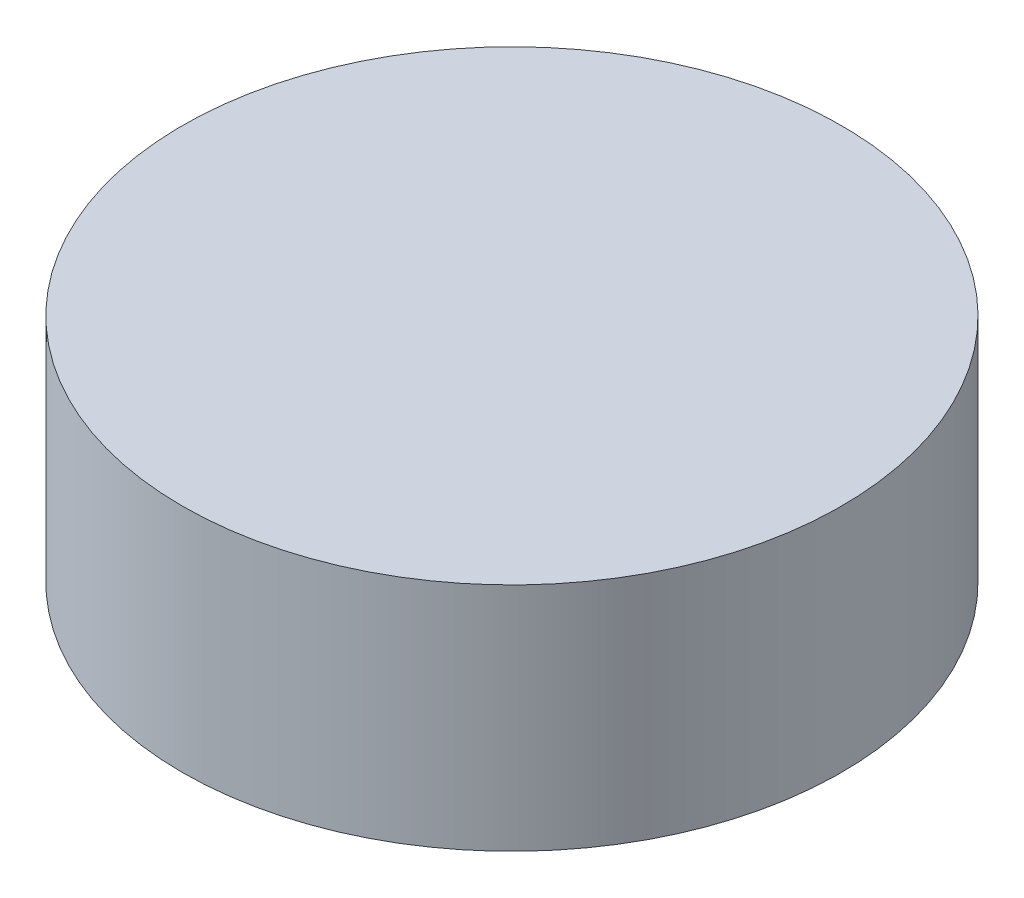
SolidWorks part; units mm, degrees
ref_plane "前视基准面" through (0, 0, 0) normal (0, 0, 1) x (1, 0, 0)
ref_plane "上视基准面" through (0, 0, 0) normal (0, 1, 0) x (1, 0, 0)
ref_plane "右视基准面" through (0, 0, 0) normal (1, 0, 0) x (0, 0, -1)
sketch "Sketch1" plane through (0, 0, 0) normal (0, 1, 0) x (1, 0, 0)
  circle A0 centre (0, 0) radius 3.9687
  dimension "D1" = 7.9375
extrude "Boss-Extrude1" add sketch "Sketch1" along normal blind 2.7781
